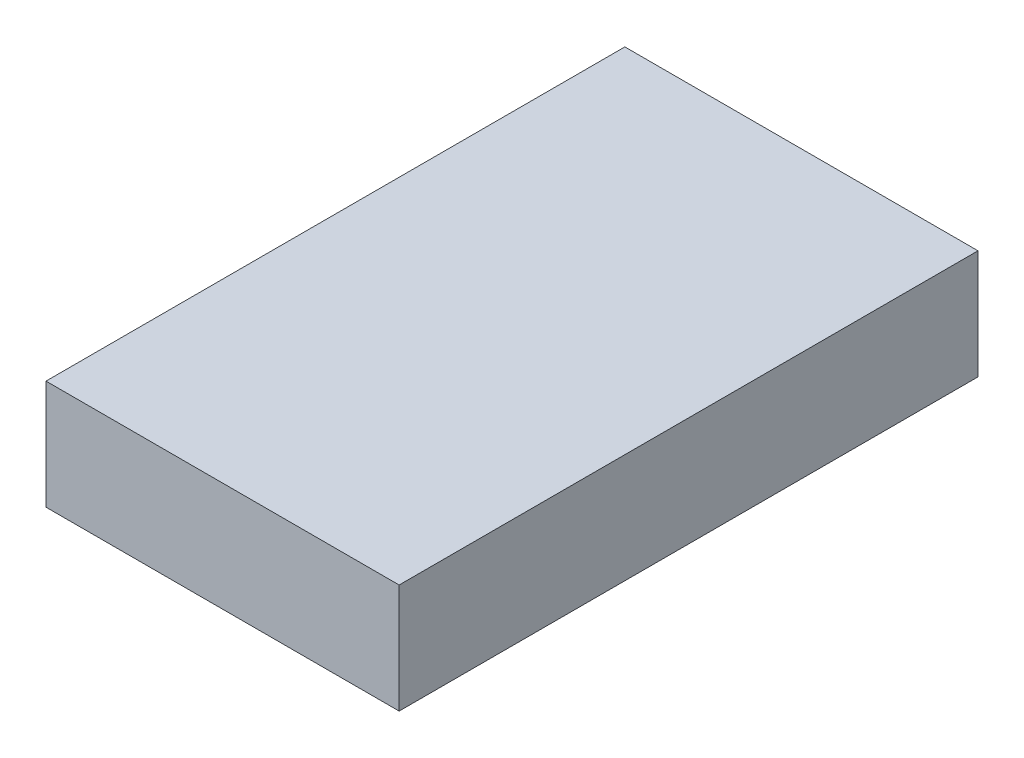
SolidWorks part; units mm, degrees
ref_plane "Front Plane" through (0, 0, 0) normal (0, 0, 1) x (1, 0, 0)
ref_plane "Top Plane" through (0, 0, 0) normal (0, 1, 0) x (1, 0, 0)
ref_plane "Right Plane" through (0, 0, 0) normal (1, 0, 0) x (0, 0, -1)
sketch "Sketch1" plane through (0, 0, 0) normal (0, 1, 0) x (1, 0, 0)
  line L1 (48.5, 79.5) -> (-48.5, 79.5)
  line L2 (48.5, 79.5) -> (48.5, -79.5)
  line L3 (48.5, -79.5) -> (-48.5, -79.5)
  line L4 (-48.5, 79.5) -> (-48.5, -79.5)
  line L5 (0, -79.5) -> (0, 79.5) construction
  line L6 (48.5, 0) -> (-48.5, 0) construction
  point P0 (0, 0)
  dimension "D1" = 97
  dimension "D2" = 159
extrude "Boss-Extrude1" add sketch "Sketch1" along normal blind 30
